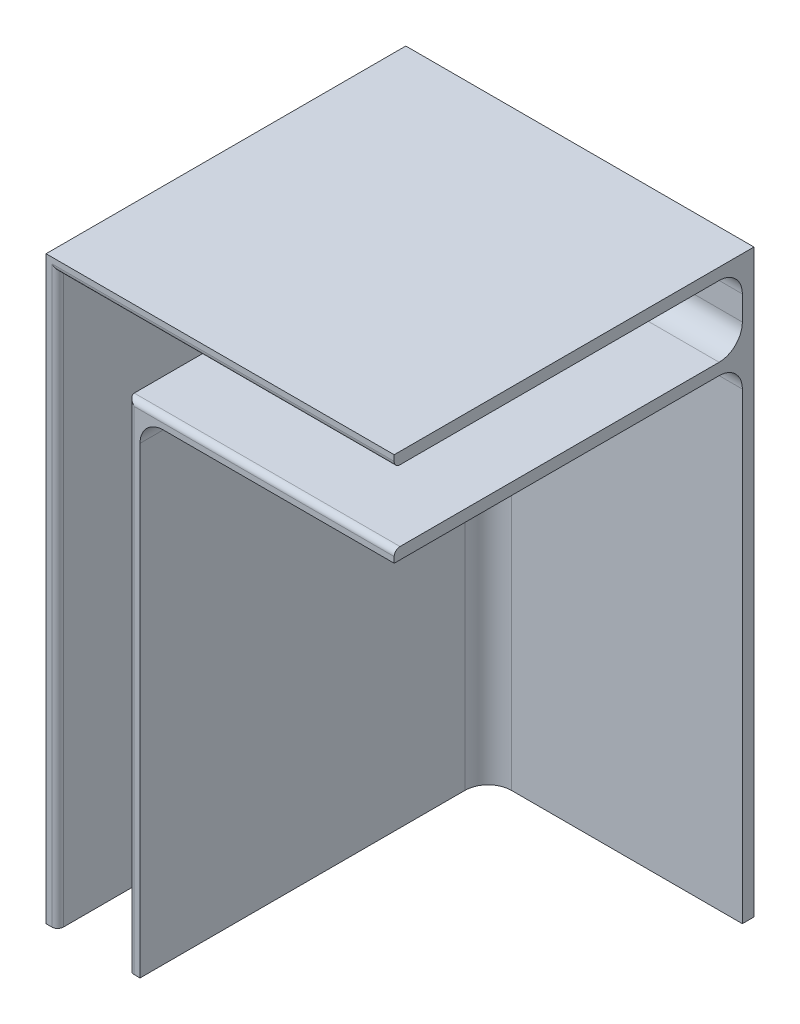
SolidWorks part; units mm, degrees
ref_plane "Front" through (0, 0, 0) normal (0, 0, 1) x (1, 0, 0)
ref_plane "Top" through (0, 0, 0) normal (0, 1, 0) x (1, 0, 0)
ref_plane "Right" through (0, 0, 0) normal (1, 0, 0) x (0, 0, -1)
sketch "Sketch1" plane through (0, 0, 0) normal (0, 0, 1) x (1, 0, 0)
  line L5 (0, 0) -> (30, 0)
  line L6 (0, 0) -> (0, 50)
  line L7 (0, 50) -> (30, 50)
  line L8 (30, 0) -> (30, 50)
  dimension "D1" = 50
  dimension "D2" = 30
extrude "Boss-Extrude1" add sketch "Sketch1" along normal blind 1
sketch "Sketch2" plane through (0, 0, 1) normal (0, 0, 1) x (1, 0, 0)
  line L5 (30, 0) -> (30, 50) construction
  line L15 (0, 50) -> (30, 50)
  line L16 (0, 50) -> (0, 49)
  line L17 (1, 49) -> (30, 49)
  line L18 (30, 50) -> (30, 49)
  line L19 (0, 0) -> (30, 0) construction
  line L21 (0, 49) -> (0, 0)
  line L22 (0, 0) -> (1, 0)
  line L23 (1, 49) -> (1, 0)
  line L25 (30, 41.9) -> (8.1, 41.9)
  line L26 (30, 41.9) -> (30, 42.9)
  line L27 (30, 42.9) -> (7.1, 42.9)
  line L28 (7.1, 41.9) -> (7.1, 42.9)
  line L30 (7.1, 41.9) -> (7.1, 0)
  line L31 (7.1, 0) -> (8.1, 0)
  line L32 (8.1, 41.9) -> (8.1, 0)
  dimension "D1" = 1
  dimension "D2" = 6.1
  dimension "D3" = 6.1
extrude "Boss-Extrude2" add sketch "Sketch2" along normal blind 30
fillet "Fillet1" radius 2 7 edges at (18.55, 42.9, 1) (7.1, 21.45, 1) (15.5, 49, 1) (1, 24.5, 1) (8.1, 41.9, 16) (8.1, 20.95, 1) (19.05, 41.9, 1)
fillet "Fillet2" radius 0.5 4 edges at (15.5, 49, 31) (18.55, 42.9, 31) (7.1, 21.45, 31) (1, 24.5, 31)
